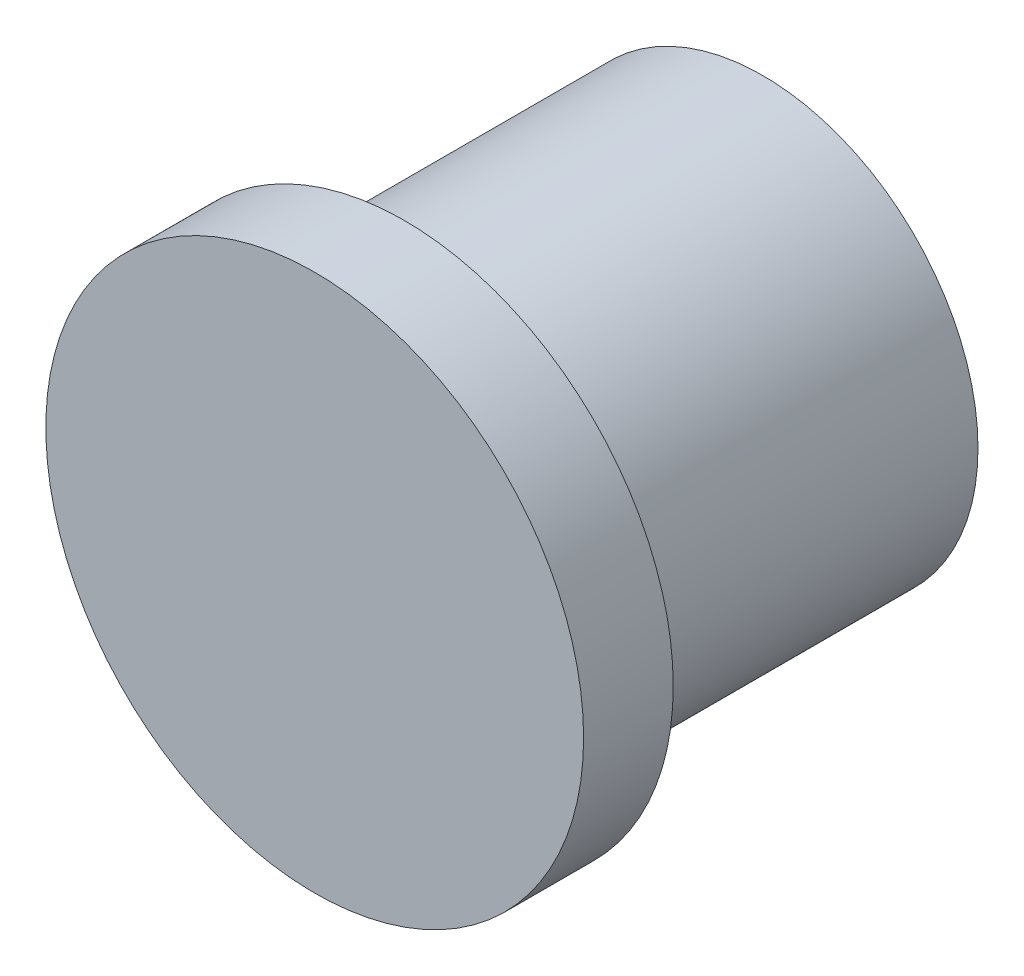
SolidWorks part; units mm, degrees
ref_plane "Front Plane" through (0, 0, 0) normal (0, 0, 1) x (1, 0, 0)
ref_plane "Top Plane" through (0, 0, 0) normal (0, 1, 0) x (1, 0, 0)
ref_plane "Right Plane" through (0, 0, 0) normal (1, 0, 0) x (0, 0, -1)
sketch "Sketch1" plane through (0, 0, 0) normal (0, 0, 1) x (1, 0, 0)
  circle A0 centre (0, 0) radius 12
  circle A1 centre (0, 0) radius 15
  dimension "D1" = 24
  dimension "D2" = 30
extrude "Boss-Extrude1" add sketch "Sketch1" along normal blind 5
sketch "Sketch2" plane through (0, 0, 5) normal (0, 0, 1) x (1, 0, 0)
  circle A0 centre (0, 0) radius 12
extrude "Boss-Extrude2" add sketch "Sketch2" against normal blind 25
